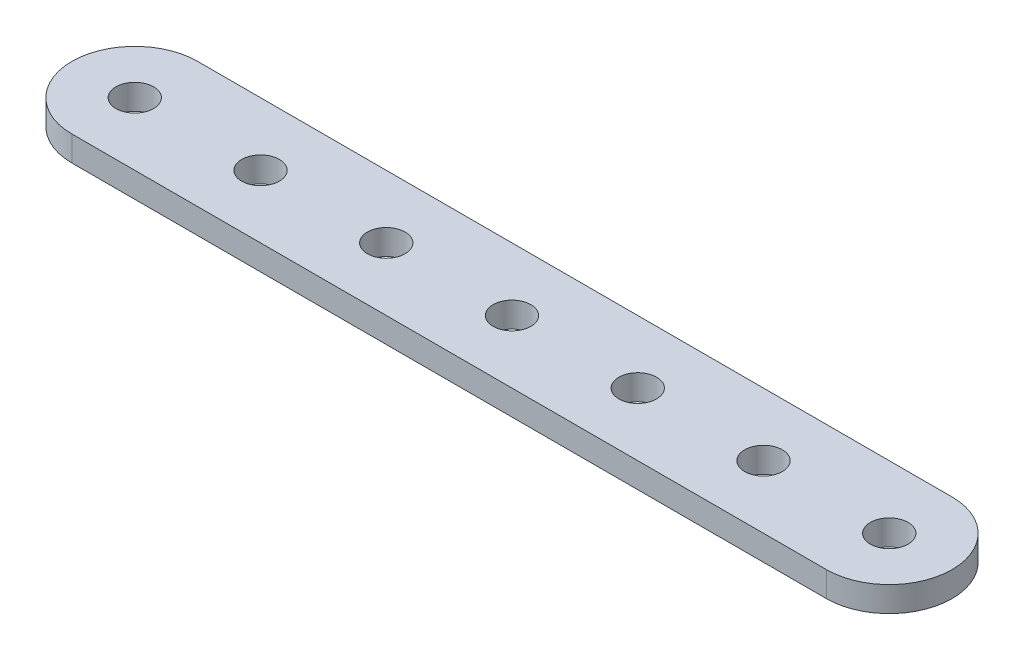
SolidWorks part; units mm, degrees
ref_plane "Front Plane" through (0, 0, 0) normal (0, 0, 1) x (1, 0, 0)
ref_plane "Top Plane" through (0, 0, 0) normal (0, 1, 0) x (1, 0, 0)
ref_plane "Right Plane" through (0, 0, 0) normal (1, 0, 0) x (0, 0, -1)
sketch "Sketch1" plane through (0, 0, 0) normal (0, 1, 0) x (1, 0, 0)
  line L0 (-150, 0) -> (150, 0) construction
  line L1 (-150, 25) -> (150, 25)
  line L2 (-150, -25) -> (150, -25)
  arc A0 (-150, 25) -> (-150, -25) centre (-150, 0) ccw
  arc A1 (150, -25) -> (150, 25) centre (150, 0) ccw
  circle A2 centre (-150, 0) radius 7.5
  circle A3 centre (150, 0) radius 7.5
  circle A4 centre (-100, 0) radius 7.5
  circle A5 centre (-50, 0) radius 7.5
  circle A6 centre (0, 0) radius 7.5
  circle A7 centre (50, 0) radius 7.5
  circle A8 centre (100, 0) radius 7.5
  point P2 (0, 0)
  dimension "D3" = 15
  dimension "D4" = 15
  dimension "D1" = 50
  dimension "D2" = 300
  dimension "D6" = 50
  dimension "D5" = 6
extrude "Boss-Extrude1" add sketch "Sketch1" along normal blind 10
